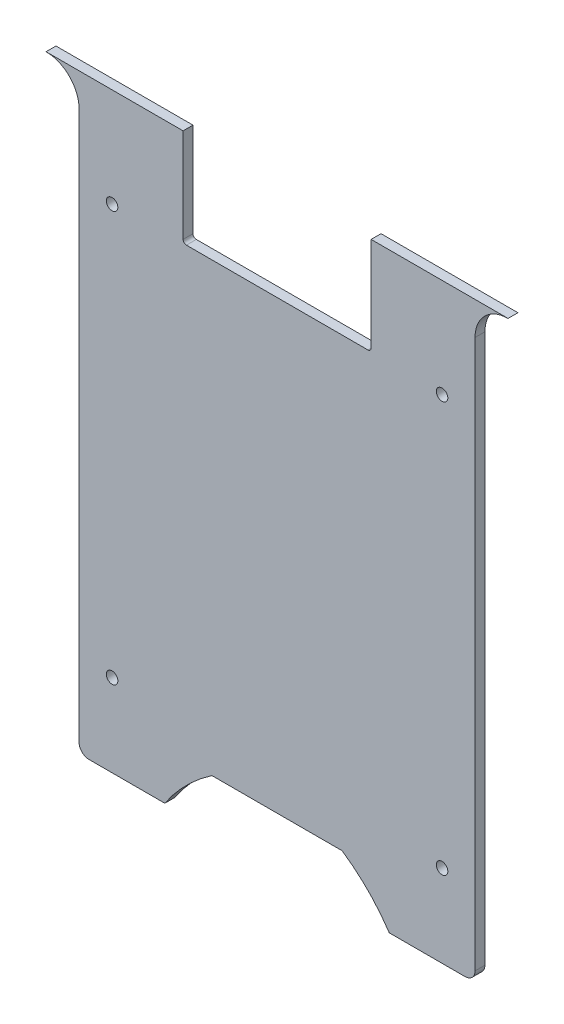
SolidWorks part; units mm, degrees
ref_plane "Front Plane" through (0, 0, 0) normal (0, 0, 1) x (1, 0, 0)
ref_plane "Top Plane" through (0, 0, 0) normal (0, 1, 0) x (1, 0, 0)
ref_plane "Right Plane" through (0, 0, 0) normal (1, 0, 0) x (0, 0, -1)
sketch "Sketch1" plane through (0, 0, 0) normal (0, 0, 1) x (1, 0, 0)
  line L0 (-27.9693, 202.4106) -> (-27.9693, 206.7114) construction
  line L1 (-22.149, 190) -> (-19.7266, 190) construction
  line L2 (28.0102, 196.8383) -> (28.0102, 196.9299) construction
  line L26 (-70, 219) -> (-28.4693, 219)
  line L27 (28.5102, 219) -> (70, 219)
  line L28 (60, 42.7463) -> (60, 209)
  line L29 (34.0107, 39.7463) -> (57, 39.7463)
  line L30 (-19.7266, 54.15) -> (19.7266, 54.15)
  line L31 (-57, 39.7463) -> (-34.0107, 39.7463)
  line L32 (-60, 209) -> (-60, 42.7463)
  line L48 (28.5102, 190.5) -> (28.5102, 219)
  line L49 (-27.4693, 189.5) -> (27.5102, 189.5)
  line L50 (-28.4693, 219) -> (-28.4693, 190.5)
  arc A0 (28.5102, 190.5) -> (27.5102, 189.5) centre (27.5102, 190.5) cw
  arc A1 (-27.4693, 189.5) -> (-28.4693, 190.5) centre (-27.4693, 190.5) cw
  arc A24 (57, 39.7463) -> (60, 42.7463) centre (57, 42.7463) ccw
  arc A25 (-60, 42.7463) -> (-57, 39.7463) centre (-57, 42.7463) ccw
  arc A26 (-60, 209) -> (-70, 219) centre (-70, 209) ccw
  arc A31 (70, 219) -> (60, 209) centre (70, 209) ccw
  circle A34 centre (-50, 189) radius 1.75
  circle A36 centre (50, 189) radius 1.75
  circle A38 centre (-50, 64.7463) radius 1.75
  circle A48 centre (50, 64.7463) radius 1.75
  parabola Q4 (19.7266, 54.15) -> (34.0107, 39.7463) focus (9.6843, 28.5899) apex (28.837, 46.3163)
  parabola Q5 (-34.0107, 39.7463) -> (-19.7266, 54.15) focus (-9.6843, 28.5899) apex (-28.837, 46.3163)
  point P7 (0, 0)
  point P8 (28.0102, 196.9299)
  point P10 (28.5102, 189.5)
  point P11 (28.837, 189.5)
  dimension "D8" = 1
  dimension "D1" = 166.2537
  dimension "D2" = 166.2537
  dimension "D3" = 22.9893
  dimension "D4" = 0.5
  dimension "D5" = 0.5
  dimension "D6" = 120
  dimension "D7" = 0.5
extrude "Boss-Extrude1" add sketch "Sketch1" along normal blind 3
